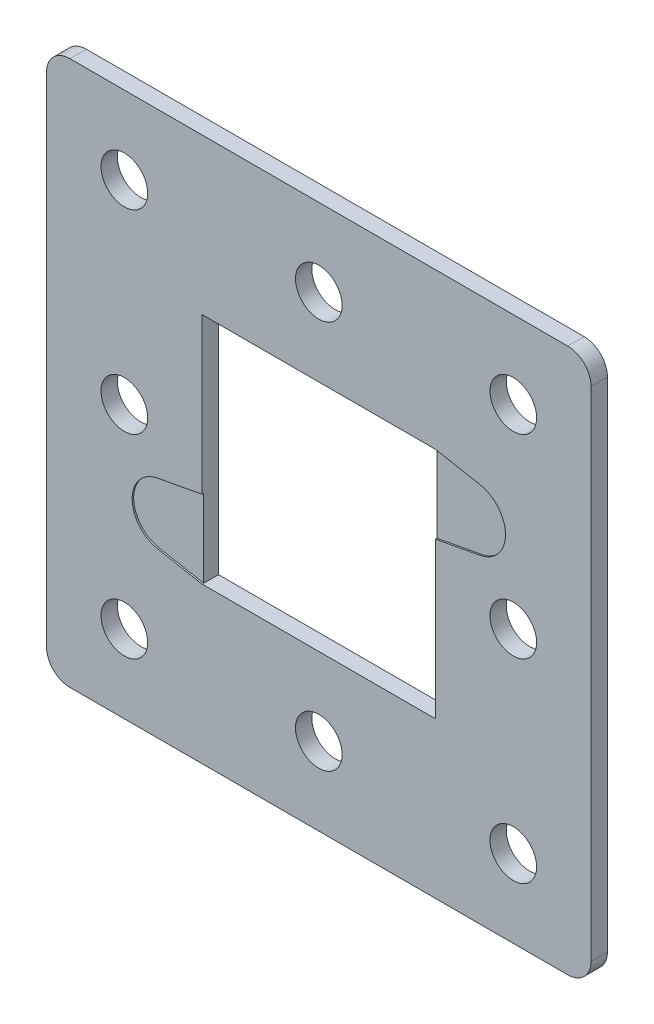
SolidWorks part; units mm, degrees
ref_plane "Front Plane" through (0, 0, 0) normal (0, 0, 1) x (1, 0, 0)
ref_plane "Top Plane" through (0, 0, 0) normal (0, 1, 0) x (1, 0, 0)
ref_plane "Right Plane" through (0, 0, 0) normal (1, 0, 0) x (0, 0, -1)
sketch "Sketch3" plane through (0, 0, 0) normal (0, 0, 1) x (1, 0, 0)
  line L1 (-35, -35) -> (35, -35)
  line L2 (-35, -35) -> (-35, 35)
  line L3 (-35, 35) -> (35, 35)
  line L4 (35, -35) -> (35, 35)
  line L5 (0, 35) -> (0, -35) construction
  line L6 (-35, 0) -> (35, 0) construction
  point P0 (0, 0)
  dimension "D1" = 70
  dimension "D2" = 70
extrude "Boss-Extrude1" add sketch "Sketch3" along normal blind 2.105
sketch "Sketch6" plane through (0, 0, 2.105) normal (0, 0, 1) x (1, 0, 0)
  line L9 (-15, -15) -> (15, -15)
  line L10 (-15, -15) -> (-15, 15)
  line L11 (-15, 15) -> (15, 15)
  line L12 (15, -15) -> (15, 15)
  line L13 (0, 15) -> (0, -15) construction
  line L14 (-15, 0) -> (15, 0) construction
  circle A0 centre (0, 25) radius 3
  circle A1 centre (25, 25) radius 3
  circle A2 centre (25, 0) radius 3
  circle A3 centre (25, -25) radius 3
  circle A4 centre (0, -25) radius 3
  circle A5 centre (-25, -25) radius 3
  circle A6 centre (-25, 0) radius 3
  circle A7 centre (-25, 25) radius 3
  point P0 (0, 0)
  point P12 (0, 0)
  point P13 (0, 0)
  dimension "D3" = 30
  dimension "D1" = 50
  dimension "D2" = 50
  dimension "D4" = 30
extrude "Cut-Extrude5" cut sketch "Sketch6" against normal blind 2.105
sketch "Sketch8" plane through (0, 0, 2.105) normal (0, 0, 1) x (1, 0, 0)
  line L0 (-15, 15) -> (-15, -15) construction
  line L1 (-35, -35) -> (35, -35) construction
  line L2 (35, 35) -> (-35, 35) construction
  line L3 (15, -15) -> (15, 15) construction
  line L5 (15, 5) -> (15, 15)
  line L6 (15, 15) -> (20.7324, 13.9324)
  line L7 (15, 5) -> (20.7324, 6.0676)
  line L8 (-15, -15) -> (-20.7324, -13.9324)
  line L9 (-15, -15) -> (-15, -5)
  line L10 (-15, -5) -> (-20.7324, -6.0676)
  arc A0 (20.7324, 6.0676) -> (20.7324, 13.9324) centre (20, 10) ccw
  arc A1 (-20.7324, -6.0676) -> (-20.7324, -13.9324) centre (-20, -10) ccw
  point P0 (0, 0)
  dimension "D3" = 25
  dimension "D5" = 8
  dimension "D6" = 8
  dimension "D1" = 5
  dimension "D2" = 25
  dimension "D4" = 5
extrude "Cut-Extrude7" cut sketch "Sketch8" against normal blind 0.2
fillet "Fillet1" radius 3 4 edges at (-35, -35, 1.0525) (-35, 35, 1.0525) (35, 35, 1.0525) (35, -35, 1.0525)
